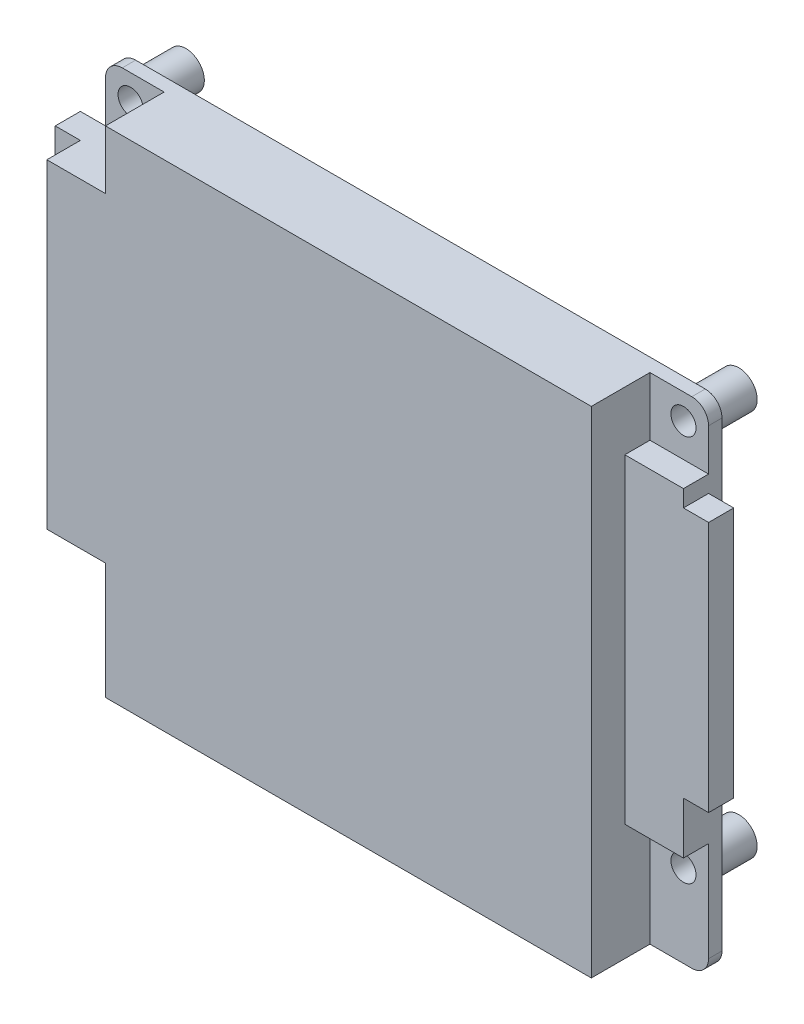
SolidWorks part; units mm, degrees
ref_plane "前视基准面" through (0, 0, 0) normal (0, 0, 1) x (1, 0, 0)
ref_plane "上视基准面" through (0, 0, 0) normal (0, 1, 0) x (1, 0, 0)
ref_plane "右视基准面" through (0, 0, 0) normal (1, 0, 0) x (0, 0, -1)
other "Configuration Table"
sketch "草图1" plane through (0, 0, 0) normal (0, 0, 1) x (1, 0, 0)
  line L0 (-12.6839, 0) -> (10.2591, 0) construction
  line L1 (0, 7.3679) -> (0, -9.886) construction
  line L3 (-34, -29.55) -> (34, -29.55)
  line L4 (-36, -27.55) -> (-36, 27.55)
  line L5 (-34, 29.55) -> (34, 29.55)
  line L6 (36, -27.55) -> (36, 27.55)
  line L7 (-36, -29.55) -> (36, 29.55) construction
  line L8 (-36, 29.55) -> (36, -29.55) construction
  arc A0 (-36, 27.55) -> (-34, 29.55) centre (-34, 27.55) cw
  arc A1 (-34, -29.55) -> (-36, -27.55) centre (-34, -27.55) cw
  arc A2 (34, -29.55) -> (36, -27.55) centre (34, -27.55) ccw
  arc A3 (34, 29.55) -> (36, 27.55) centre (34, 27.55) cw
  point P4 (0, 0)
  dimension "D3" = 2
  dimension "D1" = 59.1
  dimension "D2" = 72
extrude "凸台-拉伸1" add sketch "草图1" along normal blind 1.6
sketch "草图2" plane through (0, 0, 1.6) normal (0, 0, 1) x (1, 0, 0)
  line L0 (0, 45.1171) -> (0, -52.0099) construction
  line L1 (-33, -19.65) -> (33, -19.65) construction
  line L2 (-33, -19.65) -> (-33, 26.55) construction
  line L3 (-33, 26.55) -> (33, 26.55) construction
  line L4 (33, -19.65) -> (33, 26.55) construction
  line L5 (34, 29.55) -> (-34, 29.55) construction
  circle A0 centre (-33, 26.55) radius 1.5
  circle A1 centre (33, 26.55) radius 1.5
  circle A2 centre (-33, -19.65) radius 1.5
  circle A3 centre (33, -19.65) radius 1.5
  dimension "D4" = 3
  dimension "D1" = 46.2
  dimension "D2" = 66
  dimension "D3" = 3
extrude "切除-拉伸1" cut sketch "草图2" against normal through all
sketch "草图3" plane through (0, 0, 0) normal (0, 0, -1) x (-1, 0, 0)
  circle A0 centre (33, 26.55) radius 2.2
  circle A1 centre (33, -19.65) radius 2.2
  circle A2 centre (-33, -19.65) radius 2.2
  circle A3 centre (-33, 26.55) radius 2.2
  circle A4 centre (33, 26.55) radius 1.5 construction
  circle A5 centre (33, -19.65) radius 1.5 construction
  circle A6 centre (-33, -19.65) radius 1.5 construction
  circle A7 centre (-33, 26.55) radius 1.5 construction
  circle A8 centre (33, 26.55) radius 1.5
  circle A9 centre (33, -19.65) radius 1.5
  circle A10 centre (-33, -19.65) radius 1.5
  circle A11 centre (-33, 26.55) radius 1.5
  dimension "D1" = 4.4
extrude "凸台-拉伸2" add sketch "草图3" along normal blind 5
sketch "草图4" plane through (0, 0, 1.6) normal (0, 0, 1) x (1, 0, 0)
  line L0 (-29, 29.55) -> (-29, 22.55)
  line L1 (34, 29.55) -> (-34, 29.55) construction
  line L2 (-29, 22.55) -> (-36, 22.55)
  line L3 (-36, 27.55) -> (-36, -27.55) construction
  line L4 (-36, 22.55) -> (-36, -15.65)
  line L5 (-36, -15.65) -> (-29, -15.65)
  line L6 (-29, -15.65) -> (-29, -29.55)
  line L7 (-34, -29.55) -> (34, -29.55) construction
  line L8 (-29, -29.55) -> (29, -29.55)
  line L9 (-29, 29.55) -> (29, 29.55)
  line L10 (0, 36.5227) -> (0, -55.4511) construction
  line L11 (29, -15.65) -> (29, -29.55)
  line L12 (36, -15.65) -> (29, -15.65)
  line L13 (36, 22.55) -> (36, -15.65)
  line L14 (29, 22.55) -> (36, 22.55)
  line L15 (29, 29.55) -> (29, 22.55)
  circle A0 centre (-33, -19.65) radius 1.5 construction
  circle A1 centre (-33, 26.55) radius 1.5 construction
  point P23 (0, 29.55)
  point P24 (0, -29.55)
  dimension "D3" = 4
  dimension "D1" = 4
  dimension "D2" = 4
  dimension "D4" = 4
extrude "凸台-拉伸3" add sketch "草图4" along normal blind 7
sketch "草图5" plane through (0, 0, 0) normal (0, 0, -1) x (-1, 0, 0)
  line L0 (34, -29.55) -> (20, -29.55)
  line L1 (34, -29.55) -> (34, -23.55)
  line L2 (34, -23.55) -> (20, -23.55)
  line L3 (20, -29.55) -> (20, -23.55)
  line L4 (34, -29.55) -> (-34, -29.55) construction
  line L5 (36, 27.55) -> (36, -27.55) construction
  dimension "D1" = 14
  dimension "D2" = 6
  dimension "D3" = 2
extrude "凸台-拉伸4" add sketch "草图5" along normal blind 10
sketch "草图6" plane through (0, 0, 1.6) normal (0, 0, 1) x (1, 0, 0)
  line L0 (36, -15.65) -> (36, 22.55) construction
  line L1 (-36, 22.55) -> (-39, 22.55)
  line L2 (-36, 22.55) -> (-36, 4.55)
  line L3 (-36, 4.55) -> (-39, 4.55)
  line L4 (-39, 22.55) -> (-39, 4.55)
  line L5 (36, 20.55) -> (39, 20.55)
  line L6 (36, 20.55) -> (36, -9.45)
  line L7 (36, -9.45) -> (39, -9.45)
  line L8 (39, 20.55) -> (39, -9.45)
  line L9 (36, 22.55) -> (29, 22.55) construction
  dimension "D1" = 3
  dimension "D2" = 30
  dimension "D3" = 3
  dimension "D4" = 18
  dimension "D5" = 2
extrude "凸台-拉伸5" add sketch "草图6" along normal blind 3
sketch "草图7" plane through (0, 0, 8.6) normal (0, 0, 1) x (1, 0, 0)
  line L1 (36, -15.65) -> (29, -15.65)
  line L2 (36, -15.65) -> (36, 22.55)
  line L3 (36, 22.55) -> (29, 22.55)
  line L4 (29, -15.65) -> (29, 22.55)
extrude "切除-拉伸2" cut sketch "草图7" against normal up to surface (4 mm away) up to face at (37.5, 5.55, 4.6)
